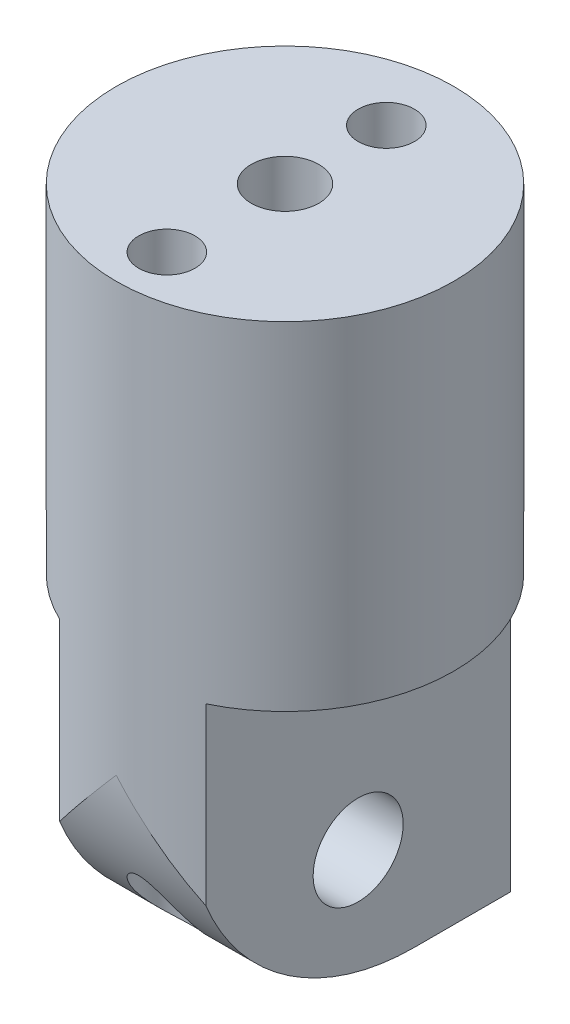
SolidWorks part; units mm, degrees
ref_plane "Front Plane" through (0, 0, 0) normal (0, 0, 1) x (1, 0, 0)
ref_plane "Top Plane" through (0, 0, 0) normal (0, 1, 0) x (1, 0, 0)
ref_plane "Right Plane" through (0, 0, 0) normal (1, 0, 0) x (0, 0, -1)
sketch "Sketch1" plane through (0, 0, 0) normal (0, 0, 1) x (1, 0, 0)
  line L1 (-3.25, 7) -> (3.25, 7)
  line L2 (-3.25, 7) -> (-3.25, -7)
  line L3 (-3.25, -7) -> (3.25, -7)
  line L4 (3.25, 7) -> (3.25, -7)
  line L5 (-3.25, 7) -> (3.25, -7) construction
  line L6 (-3.25, -7) -> (3.25, 7) construction
  point P0 (0, 0)
  dimension "D1" = 6.5
  dimension "D2" = 14
extrude "Boss-Extrude1" add sketch "Sketch1" along normal blind 15
fillet "Fillet1" radius 10 1 edges at (0, -7, 15)
sketch "Sketch2" plane through (3.25, 0, 0) normal (1, 0, 0) x (0, 0, -1)
  line L0 (-7.5, 7) -> (-7.5, -6.6825) construction
  line L1 (-15, 7) -> (0, 7) construction
  arc A0 (-15, 3) -> (-5, -7) centre (-5, 3) ccw construction
  circle A1 centre (-7.5, -2) radius 2
  dimension "D1" = 4
  dimension "D2" = 4.6825
extrude "Cut-Extrude1" cut sketch "Sketch2" against normal through all
sketch "Sketch4" plane through (0, 7, 0) normal (0, 1, 0) x (1, 0, 0)
  line L0 (0, 0) -> (0, -15) construction
  line L1 (3.25, 0) -> (-3.25, 0) construction
  line L2 (3.25, -15) -> (-3.25, -15) construction
  circle A0 centre (0, -7.5) radius 7.5
  dimension "D1" = 15
extrude "Boss-Extrude2" add sketch "Sketch4" along normal blind 15
sketch "Sketch6" plane through (0, 0, 0) normal (0, 0, -1) x (-1, 0, 0)
  line L0 (7.5, 22) -> (-7.5, 22) construction
  line L1 (3.5, 22) -> (-3.5, 22)
  line L2 (3.5, 22) -> (3.5, 9.32)
  line L3 (3.5, 9.32) -> (-3.5, 9.32)
  line L4 (-3.5, 22) -> (-3.5, 9.32)
  point P4 (0, 9.32)
  dimension "D1" = 7
  dimension "D2" = 12.68
extrude "Cut-Extrude2" cut sketch "Sketch6" against normal through all
sketch "Sketch7" plane through (0, 7, 0) normal (0, 1, 0) x (1, 0, 0)
  line L2 (-3.25, -14.2593) -> (-3.25, -15)
  line L3 (-3.25, -15) -> (0, -15)
  line L4 (-3.25, -14.2593) -> (-3.25, -15)
  line L5 (-3.25, -15) -> (0, -15)
  line L6 (0, -15) -> (3.25, -15)
  line L7 (3.25, -15) -> (3.25, -14.2593)
  line L8 (0, -15) -> (3.25, -15)
  line L9 (3.25, -15) -> (3.25, -14.2593)
  line L10 (0, 0) -> (-3.25, 0)
  line L11 (-3.25, 0) -> (-3.25, -0.7407)
  line L12 (0, 0) -> (-3.25, 0)
  line L13 (-3.25, 0) -> (-3.25, -0.7407)
  line L14 (3.25, -0.7407) -> (3.25, 0)
  line L15 (3.25, 0) -> (0, 0)
  line L16 (3.25, -0.7407) -> (3.25, 0)
  line L17 (3.25, 0) -> (0, 0)
  arc A1 (-3.25, -14.2593) -> (0, -15) centre (0, -7.5) ccw
  arc A2 (-3.25, -14.2593) -> (0, -15) centre (0, -7.5) ccw
  arc A3 (0, -15) -> (3.25, -14.2593) centre (0, -7.5) ccw
  arc A4 (0, -15) -> (3.25, -14.2593) centre (0, -7.5) ccw
  arc A5 (0, 0) -> (-3.25, -0.7407) centre (0, -7.5) ccw
  arc A6 (0, 0) -> (-3.25, -0.7407) centre (0, -7.5) ccw
  arc A7 (3.25, -0.7407) -> (0, 0) centre (0, -7.5) ccw
  arc A8 (3.25, -0.7407) -> (0, 0) centre (0, -7.5) ccw
  dimension "D1" = 0
  dimension "D2" = 0
  dimension "D3" = 0
  dimension "D4" = 0
extrude "Cut-Extrude3" cut sketch "Sketch7" against normal through all contours A6 L12 L13 | A8 L16 L17 | A4 L8 L9
sketch "Sketch8" plane through (-3.5, 0, 0) normal (1, 0, 0) x (0, 0, -1)
  line L0 (-7.5, 9.32) -> (-7.5, 22) construction
  line L1 (-14.1332, 9.32) -> (-0.8668, 9.32) construction
  line L2 (-0.8668, 22) -> (-14.1332, 22) construction
  circle A0 centre (-7.5, 17) radius 1.5
  dimension "D2" = 3
  dimension "D1" = 5
ref_plane "Plane1" through (6.15, 0, 0) normal (-1, 0, 0) x (0, 0, 1)
ref_plane "Plane2" through (-5, 0, 0) normal (1, 0, 0) x (0, 0, -1)
sketch "Sketch11" plane through (0, -7, 0) normal (0, -1, 0) x (1, 0, 0)
  line L0 (3.25, 5) -> (-3.25, 5) construction
  circle A1 centre (0, 3) radius 1.25
  circle A3 centre (0, 12.7488) radius 1.25
  dimension "D1" = 2
extrude "Cut-Extrude7" cut sketch "Sketch11" against normal blind 24 contours A3 | A1
sketch "Sketch12" plane through (0, 9.32, 0) normal (0, 1, 0) x (1, 0, 0)
  line L2 (3.5, -14.1332) -> (3.5, -0.8668)
  line L3 (-3.5, -0.8668) -> (-3.5, -14.1332)
  line L4 (3.5, -14.1332) -> (3.5, -0.8668)
  line L5 (-3.5, -0.8668) -> (-3.5, -14.1332)
  circle A0 centre (0, -3) radius 1.25 construction
  circle A1 centre (0, -3) radius 1.25
  arc A2 (3.5, -0.8668) -> (-3.5, -0.8668) centre (0, -7.5) ccw
  arc A3 (-3.5, -14.1332) -> (3.5, -14.1332) centre (0, -7.5) ccw
  arc A4 (3.5, -0.8668) -> (-3.5, -0.8668) centre (0, -7.5) ccw
  arc A5 (-3.5, -14.1332) -> (3.5, -14.1332) centre (0, -7.5) ccw
  circle A6 centre (0, -12.7488) radius 1.25 construction
  circle A7 centre (0, -12.7488) radius 1.25
  dimension "D1" = 0
extrude "Boss-Extrude3" add sketch "Sketch12" along normal up to surface (12.68 mm away) up to face at (-5.5, 22, 7.5)
sketch "Sketch13" plane through (0, 22, 0) normal (0, 1, 0) x (1, 0, 0)
  circle A0 centre (0, -7.5) radius 1.5
  dimension "D1" = 3
extrude "Cut-Extrude8" cut sketch "Sketch13" against normal blind 6
